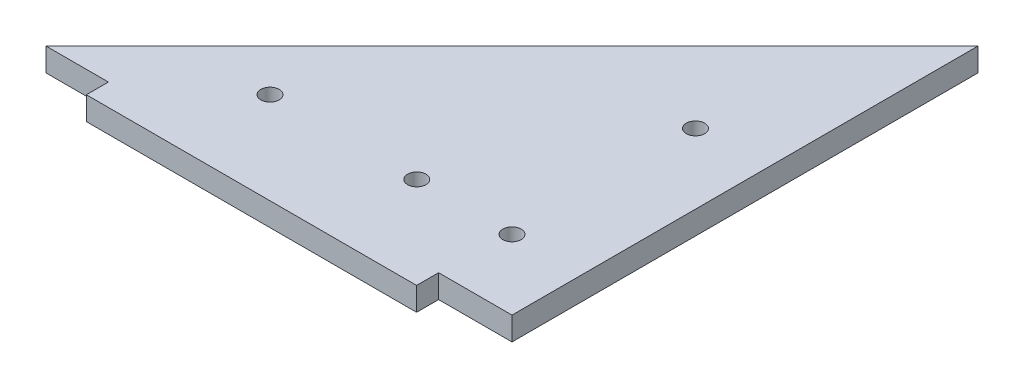
SolidWorks part; units mm, degrees
ref_plane "Front Plane" through (0, 0, 0) normal (0, 0, 1) x (1, 0, 0)
ref_plane "Top Plane" through (0, 0, 0) normal (0, 1, 0) x (1, 0, 0)
ref_plane "Right Plane" through (0, 0, 0) normal (1, 0, 0) x (0, 0, -1)
sketch "Sketch1" plane through (0, 0, 0) normal (0, 1, 0) x (1, 0, 0)
  line L1 (17, -6) -> (107, -6)
  line L2 (107, -6) -> (107, 0)
  line L3 (107, 0) -> (127, 0)
  line L4 (127, 0) -> (127, 127)
  line L5 (127, 127) -> (0, 0)
  line L6 (0, 0) -> (17, 0)
  line L7 (17, 0) -> (17, -6)
  circle A0 centre (42, 19.05) radius 2.5
  circle A1 centre (82, 19.05) radius 2.5
  circle A2 centre (107.95, 19.05) radius 2.5
  circle A3 centre (107.95, 69.05) radius 2.5
  point P16 (0, 0)
  point P17 (0, 0)
  dimension "D6" = 5
  dimension "D7" = 5
  dimension "D11" = 5
  dimension "D12" = 5
  dimension "D1" = 127
  dimension "D2" = 6
  dimension "D3" = 90
  dimension "D4" = 127
  dimension "D5" = 20
  dimension "D8" = 19.05
  dimension "D9" = 40
  dimension "D10" = 45
  dimension "D13" = 19.05
  dimension "D14" = 50
extrude "Boss-Extrude1" add sketch "Sketch1" along normal blind 6.35
